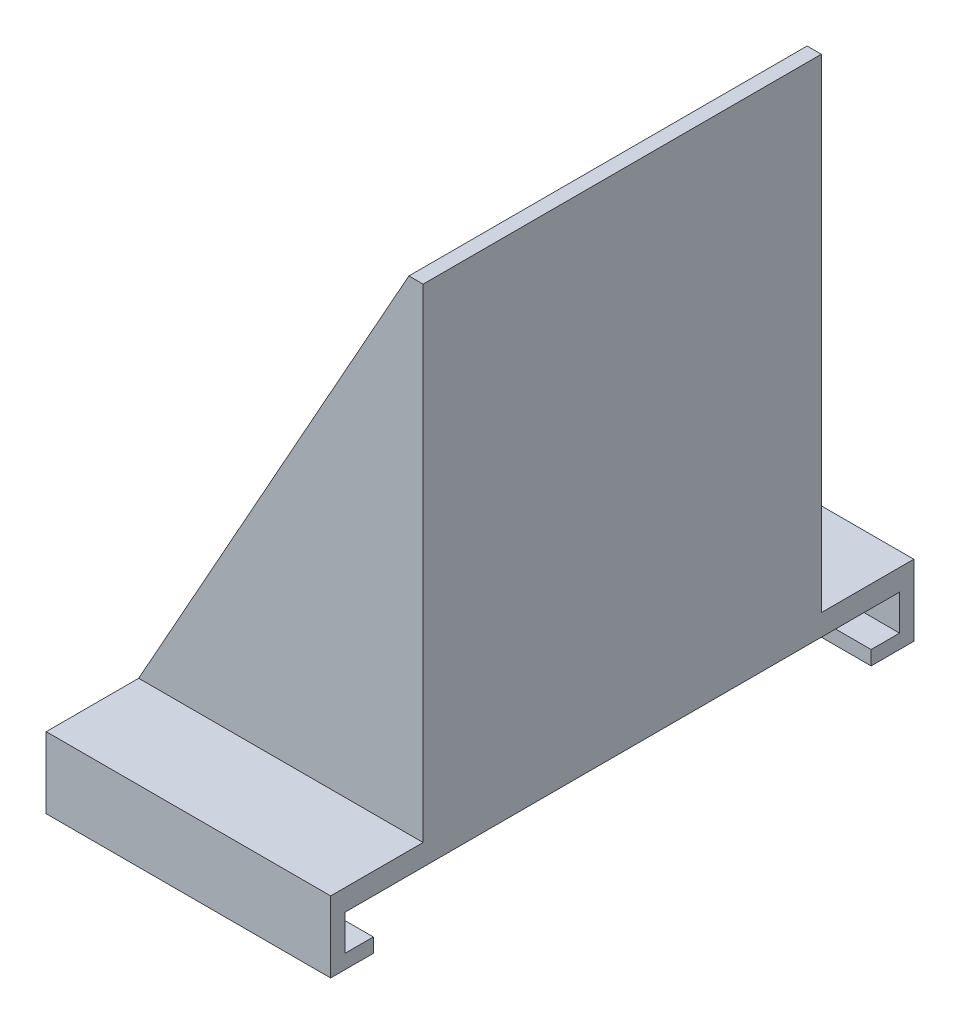
SolidWorks part; units mm, degrees
ref_plane "Alzado" through (0, 0, 0) normal (0, 0, 1) x (1, 0, 0)
ref_plane "Planta" through (0, 0, 0) normal (0, 1, 0) x (1, 0, 0)
ref_plane "Vista lateral" through (0, 0, 0) normal (1, 0, 0) x (0, 0, -1)
sketch "Croquis1" plane through (0, 0, 0) normal (0, 1, 0) x (1, 0, 0)
  line L1 (32.1489, 23.1773) -> (52.1489, 23.1773)
  line L2 (32.1489, 23.1773) -> (32.1489, -17.8227)
  line L3 (32.1489, -17.8227) -> (52.1489, -17.8227)
  line L4 (52.1489, 23.1773) -> (52.1489, -17.8227)
  dimension "D1" = 41
  dimension "D2" = 20
extrude "Saliente-Extruir1" add sketch "Croquis1" along normal blind 1.5
sketch "Croquis3" plane through (52.1489, 0, 0) normal (1, 0, 0) x (0, 0, -1)
  line L0 (-17.8227, 0) -> (-17.8227, -3.5)
  line L1 (-17.8227, -3.5) -> (-14.8227, -3.5)
  line L2 (-14.8227, -3.5) -> (-14.8227, -2.5)
  line L3 (-14.8227, -2.5) -> (-16.8227, -2.5)
  line L4 (-16.8227, -2.5) -> (-16.8227, 0)
  line L7 (22.1773, -2.5) -> (22.1773, 0)
  line L8 (20.1773, -2.5) -> (22.1773, -2.5)
  line L9 (20.1773, -3.5) -> (20.1773, -2.5)
  line L10 (23.1773, -3.5) -> (20.1773, -3.5)
  line L11 (23.1773, 0) -> (23.1773, -3.5)
  line L12 (-17.8227, 0) -> (-16.8227, 0)
  line L13 (22.1773, 0) -> (23.1773, 0)
  dimension "D1" = 3.5
  dimension "D2" = 3
  dimension "D3" = 1
extrude "Saliente-Extruir3" add sketch "Croquis3" against normal blind 20
sketch "Croquis4" plane through (52.1489, 0, 0) normal (1, 0, 0) x (0, 0, -1)
  line L1 (-11.3227, 1.5) -> (16.6773, 1.5)
  line L3 (-11.3227, 35.5) -> (16.6773, 35.5)
  line L4 (16.6773, 1.5) -> (16.6773, 35.5)
  line L5 (-11.3227, 1.5) -> (-11.3227, 35.5)
  dimension "D1" = 28
  dimension "D2" = 34
  dimension "D3" = 6.5
extrude "Saliente-Extruir4" add sketch "Croquis4" against normal blind 1
sketch "Croquis5" plane through (0, 0, 11.3227) normal (0, 0, 1) x (1, 0, 0)
  line L0 (51.1489, 35.5) -> (32.1489, 1.5)
  line L1 (32.1489, 1.5) -> (51.1489, 1.5)
  line L2 (51.1489, 1.5) -> (51.1489, 35.5)
extrude "Saliente-Extruir5" add sketch "Croquis5" against normal blind 1
sketch "Croquis6" plane through (0, 0, -16.6773) normal (0, 0, -1) x (-1, 0, 0)
  line L0 (-51.1489, 35.5) -> (-32.1489, 1.5)
  line L1 (-32.1489, 1.5) -> (-51.1489, 1.5)
  line L2 (-51.1489, 1.5) -> (-51.1489, 35.5)
extrude "Saliente-Extruir6" add sketch "Croquis6" against normal blind 1
sketch "Croquis7" plane through (0, 0, 11.3227) normal (0, 0, 1) x (1, 0, 0)
  line L0 (52.1489, 1.5) -> (52.1489, 3.5)
  line L1 (52.1489, 35.5) -> (52.1489, 1.5) construction
  line L2 (52.1489, 3.5) -> (33.2666, 3.5)
  line L3 (51.1489, 35.5) -> (32.1489, 1.5) construction
  line L4 (33.2666, 3.5) -> (32.1489, 1.5)
  line L5 (32.1489, 1.5) -> (52.1489, 1.5)
  dimension "D1" = 2
extrude "Saliente-Extruir7" add sketch "Croquis7" against normal blind 28
